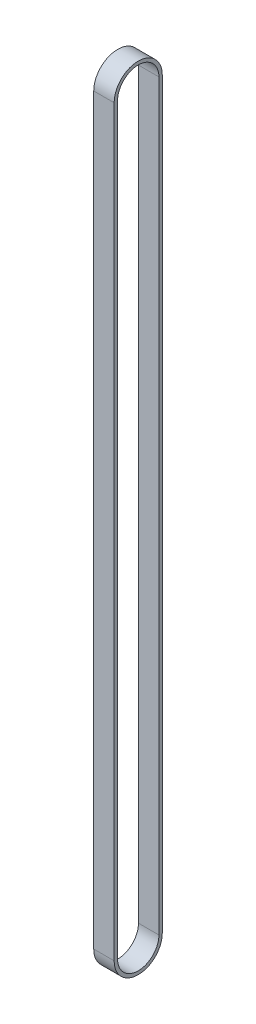
SolidWorks part; units mm, degrees
material "6063-T5"
ref_plane "Front Plane" through (0, 0, 0) normal (1, 0, 0) x (0, 1, 0)
ref_plane "Top Plane" through (0, 0, 0) normal (0, 0, 1) x (0, 1, 0)
ref_plane "Right Plane" through (0, 0, 0) normal (0, 1, 0) x (-1, 0, 0)
sketch "Sketch1" plane through (0, 0, 0) normal (1, 0, 0) x (0, 1, 0)
  line L0 (-110, 0) -> (110, 0) construction
  line L1 (-110, 6.125) -> (110, 6.125)
  line L2 (-110, -6.125) -> (110, -6.125)
  line L3 (-110, 7.125) -> (110, 7.125)
  line L4 (-110, -7.125) -> (110, -7.125)
  arc A0 (-110, 6.125) -> (-110, -6.125) centre (-110, 0) ccw
  arc A1 (110, -6.125) -> (110, 6.125) centre (110, 0) ccw
  arc A2 (110, -7.125) -> (110, 7.125) centre (110, 0) ccw
  arc A3 (-110, 7.125) -> (-110, -7.125) centre (-110, 0) ccw
  point P2 (0, 0)
  dimension "D2" = 6.125
  dimension "D1" = 220
  dimension "D3" = 1
extrude "Boss-Extrude1" add sketch "Sketch1" along normal blind 6.05
